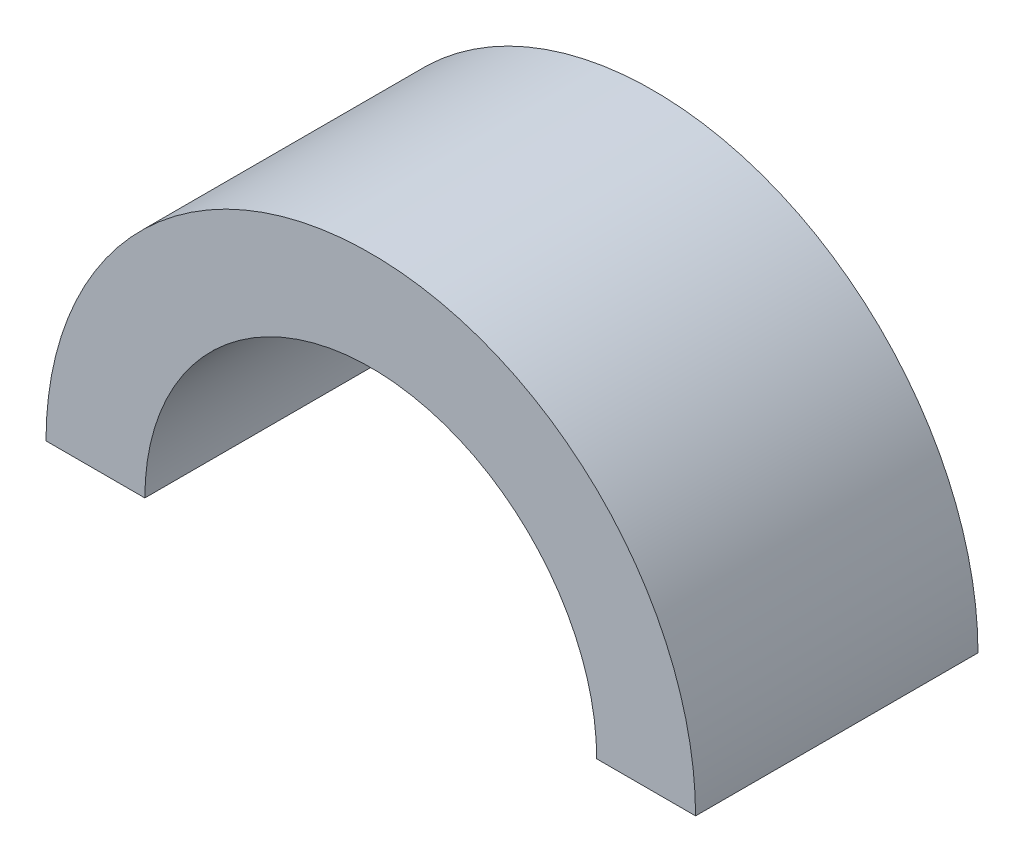
SolidWorks part; units mm, degrees
ref_plane "Front Plane" through (0, 0, 0) normal (0, 0, 1) x (1, 0, 0)
ref_plane "Top Plane" through (0, 0, 0) normal (0, 1, 0) x (1, 0, 0)
ref_plane "Right Plane" through (0, 0, 0) normal (1, 0, 0) x (0, 0, -1)
sketch "Sketch1" plane through (0, 0, 0) normal (0, 0, 1) x (1, 0, 0)
  line L0 (46, 23) -> (39, 23)
  line L1 (7, 23) -> (0, 23)
  arc A0 (0, 23) -> (46, 23) centre (23, 23) cw
  arc A1 (39, 23) -> (7, 23) centre (23, 23) ccw
  dimension "D1" = 23
  dimension "D2" = 16
extrude "Profile" add sketch "Sketch1" along normal blind 20
equation "\"Profile_Depth\"= 20mm"
equation "\"D1@Profile\" = \"Profile_Depth\""
equation "\"Profile_Sketch_1\"= 23mm"
equation "\"D1@Sketch1\" = \"Profile_Sketch_1\""
equation "\"Profile_Sketch_2\"= 16mm"
equation "\"D2@Sketch1\" = \"Profile_Sketch_2\""
equation "\"EnvelopeWidth\"= 46mm"
equation "\"EnvelopeHeight\"= 46mm"
